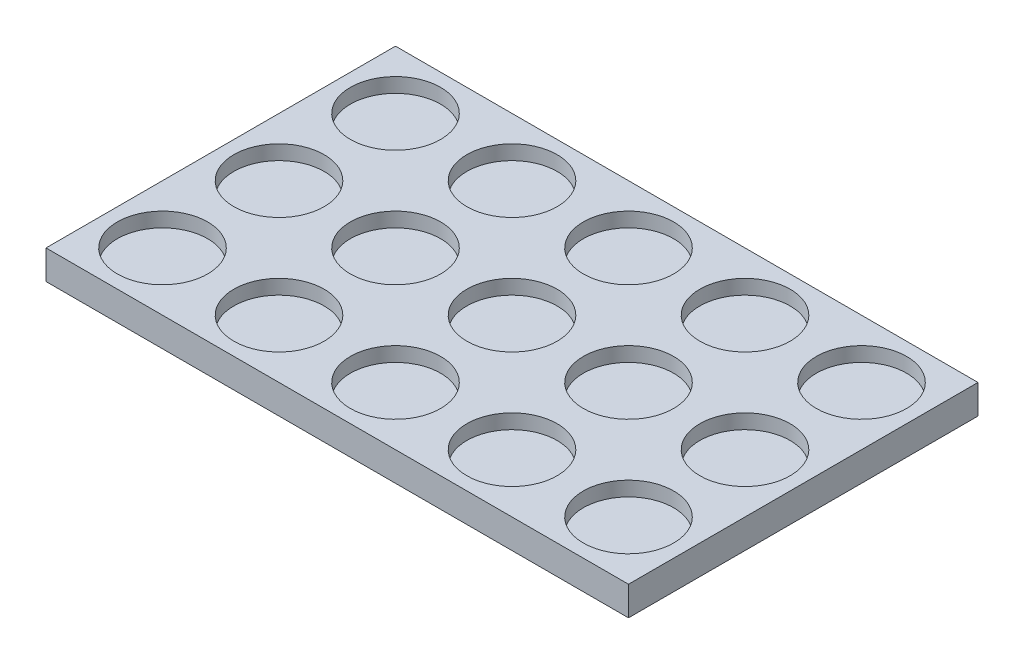
SolidWorks part; units mm, degrees
ref_plane "Front Plane" through (0, 0, 0) normal (0, 0, 1) x (1, 0, 0)
ref_plane "Top Plane" through (0, 0, 0) normal (0, 1, 0) x (1, 0, 0)
ref_plane "Right Plane" through (0, 0, 0) normal (1, 0, 0) x (0, 0, -1)
sketch "Sketch1" plane through (0, 0, 0) normal (0, 1, 0) x (1, 0, 0)
  line L0 (-254, 152.4) -> (254, -152.4) construction
  line L1 (-254, 152.4) -> (254, 152.4)
  line L2 (-254, 152.4) -> (-254, -152.4)
  line L3 (-254, -152.4) -> (254, -152.4)
  line L4 (254, 152.4) -> (254, -152.4)
  dimension "D1" = 304.8
  dimension "D2" = 508
extrude "Boss-Extrude1" add sketch "Sketch1" along normal blind 25.4
sketch "Sketch2" plane through (0, 25.4, 0) normal (0, 1, 0) x (1, 0, 0)
  line L0 (-254, -152.4) -> (254, -152.4) construction
  line L1 (-254, 152.4) -> (-254, -152.4) construction
  circle A0 centre (-203.2, -101.6) radius 39.37
  dimension "D3" = 78.74
  dimension "D1" = 50.8
  dimension "D2" = 50.8
extrude "Cut-Extrude1" cut sketch "Sketch2" against normal blind 12.7
pattern_linear "LPattern1" count 5 spacing 101.6 along (1, 0, 0) count 3 spacing 101.6 along (0, 0, -1) of "Cut-Extrude1"
